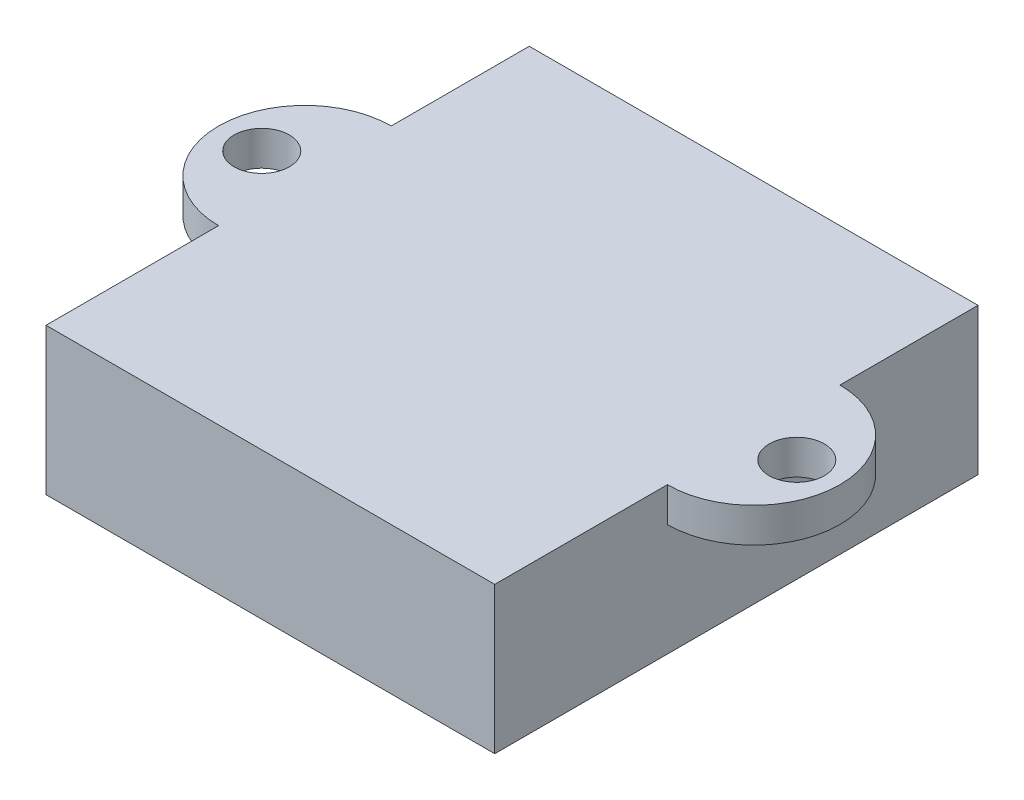
SolidWorks part; units mm, degrees
ref_plane "Front Plane" through (0, 0, 0) normal (0, 0, 1) x (1, 0, 0)
ref_plane "Top Plane" through (0, 0, 0) normal (0, 1, 0) x (1, 0, 0)
ref_plane "Right Plane" through (0, 0, 0) normal (1, 0, 0) x (0, 0, -1)
sketch "Sketch1" plane through (0, 0, 0) normal (0, 1, 0) x (1, 0, 0)
  line L1 (-13, -14) -> (13, -14)
  line L2 (-13, -14) -> (-13, 14)
  line L3 (-13, 14) -> (13, 14)
  line L4 (13, -14) -> (13, 14)
  line L5 (-13, -14) -> (13, 14) construction
  line L6 (-13, 14) -> (13, -14) construction
  point P0 (0, 0)
  dimension "D1" = 26
  dimension "D2" = 28
extrude "Boss-Extrude1" add sketch "Sketch1" along normal blind 8.5
sketch "Sketch2" plane through (0, 8.5, 0) normal (0, 1, 0) x (1, 0, 0)
  line L0 (-15.5, 1) -> (15.5, 1) construction
  line L1 (-13, -14) -> (13, -14) construction
  line L2 (13, -14) -> (13, 14) construction
  line L3 (-13, 14) -> (-13, -14) construction
  circle A0 centre (-13, 1) radius 5
  circle A1 centre (13, 1) radius 5
  point P3 (0, 1)
  dimension "D3" = 10
  dimension "D1" = 31
  dimension "D2" = 15
extrude "Boss-Extrude2" add sketch "Sketch2" against normal blind 2
hole_wizard "M3 Clearance Hole1" positions "Sketch3" profile "Sketch4" hole size "M3" standard "ANSI Metric" end condition through all
sketch "Sketch3" plane through (0, 8.5, 0) normal (0, 1, 0) x (1, 0, 0)
  point P0 (-15.5, 1)
  point P3 (15.5, 1)
sketch "Sketch4" plane through (-15.5, 8.5, -1) normal (1, 0, 0) x (0, 0, 1)
  line L0 (0, 0) -> (0, 8.5)
  line L1 (0, 8.5) -> (1.6, 8.5)
  line L2 (1.6, 8.5) -> (1.6, 0)
  line L5 (1.6, 0) -> (0, 0)
  line L11 (0, -6.35) -> (0, 107.95) construction
  dimension "Thru Hole Dia." = 3.2
  dimension "Thru Hole Depth" = 8.5
